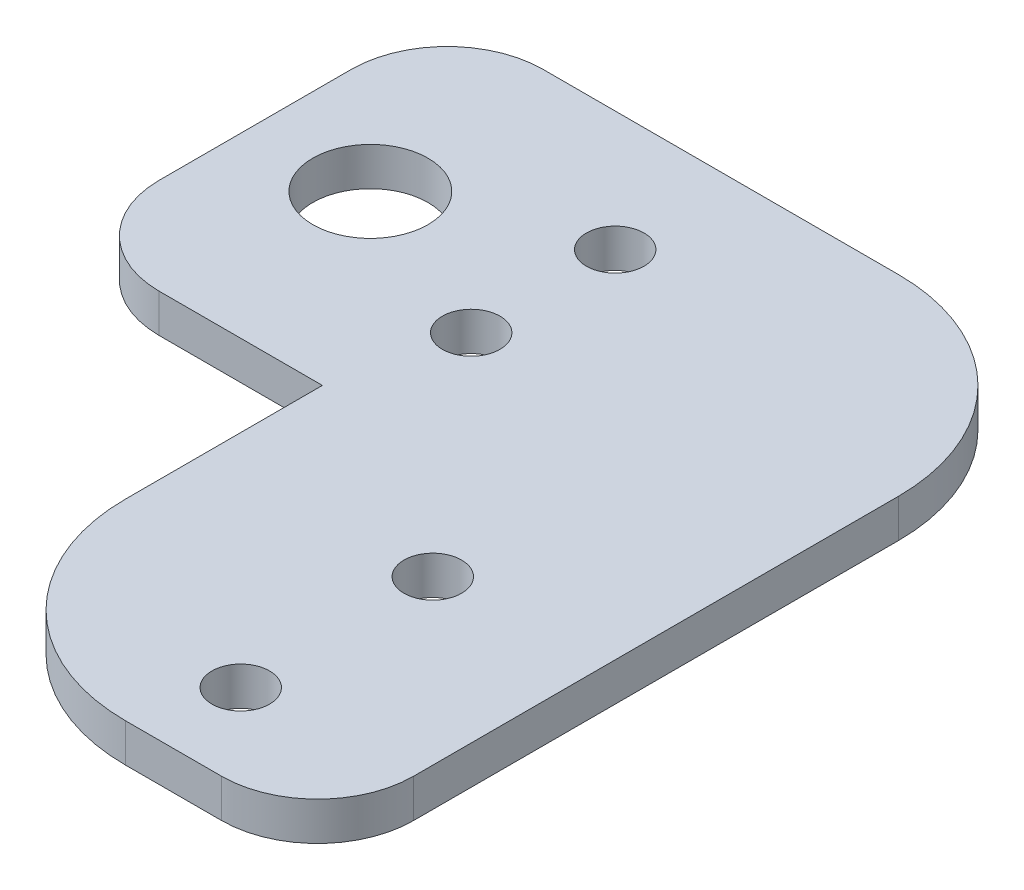
SolidWorks part; units mm, degrees
ref_plane "Front Plane" through (0, 0, 0) normal (0, 0, 1) x (1, 0, 0)
ref_plane "Top Plane" through (0, 0, 0) normal (0, 1, 0) x (1, 0, 0)
ref_plane "Right Plane" through (0, 0, 0) normal (1, 0, 0) x (0, 0, -1)
sketch "Sketch1" plane through (0, 0, 0) normal (0, 1, 0) x (1, 0, 0)
  line L1 (-12.5, 10) -> (12.5, 10)
  line L2 (-12.5, 10) -> (-12.5, -10)
  line L3 (-12.5, -10) -> (12.5, -10)
  line L4 (12.5, 10) -> (12.5, -10)
  line L5 (-12.5, 10) -> (12.5, -10) construction
  line L6 (-12.5, -10) -> (12.5, 10) construction
  point P0 (0, 0)
  point P5 (0, 0)
  dimension "D1" = 25
  dimension "D2" = 20
extrude "Boss-Extrude1" add sketch "Sketch1" along normal blind 2
sketch "Sketch2" plane through (0, 2, 0) normal (0, 1, 0) x (1, 0, 0)
  line L0 (12.5, -10) -> (12.5, 10) construction
  circle A0 centre (-6.5, 0) radius 1.5
  circle A1 centre (2.5, 3.75) radius 1.5
  circle A2 centre (2.5, -3.75) radius 1.5
  point P9 (0, 0)
  dimension "D1" = 3
  dimension "D4" = 3
  dimension "D5" = 3
  dimension "D2" = 19
  dimension "D3" = 7.5
  dimension "D6" = 3.75
  dimension "D7" = 9
extrude "Cut-Extrude1" cut sketch "Sketch2" against normal up to next
sketch "Sketch3" plane through (0, 0, 0) normal (0, -1, 0) x (-1, 0, 0)
  circle A0 centre (6.5, 0) radius 3
  circle A1 centre (6.5, 0) radius 1.5 construction
  dimension "D1" = 6
extrude "Cut-Extrude2" cut sketch "Sketch3" against normal up to next
sketch "Sketch4" plane through (0, 2, 0) normal (0, 1, 0) x (1, 0, 0)
  line L1 (21, -30.25) -> (1, -30.25)
  line L2 (21, -30.25) -> (21, -5.25)
  line L3 (21, -5.25) -> (1, -5.25)
  line L4 (1, -30.25) -> (1, -5.25)
  line L5 (21, -30.25) -> (1, -5.25) construction
  line L6 (21, -5.25) -> (1, -30.25) construction
  circle A0 centre (2.5, -3.75) radius 1.5 construction
  point P0 (11, -17.75)
  dimension "D1" = 25
  dimension "D2" = 20
extrude "Boss-Extrude2" add sketch "Sketch4" against normal blind 2
sketch "Sketch5" plane through (0, 2, 0) normal (0, 1, 0) x (1, 0, 0)
  line L0 (12.5, 10) -> (12.5, -5.25)
  line L1 (12.5, -5.25) -> (21, -5.25)
  line L2 (21, -5.25) -> (12.5, 10)
  point P4 (0, 0)
  point P6 (0, 0)
  point P8 (0, 0)
  point P10 (0, 0)
extrude "Boss-Extrude3" add sketch "Sketch5" against normal blind 2
sketch "Sketch6" plane through (0, 2, 0) normal (0, 1, 0) x (1, 0, 0)
  circle A0 centre (12.5, -15.75) radius 1.5
  circle A1 centre (2.5, -3.75) radius 1.5 construction
  circle A2 centre (12.5, -25.75) radius 1.5
  point P6 (0, 0)
  point P7 (0, 0)
  dimension "D1" = 3
  dimension "D2" = 10
  dimension "D4" = 3
  dimension "D3" = 12
  dimension "D5" = 10
extrude "Cut-Extrude3" cut sketch "Sketch6" against normal blind 2
sketch "Sketch7" plane through (0, 2, 0) normal (0, 1, 0) x (1, 0, 0)
  line L1 (12.5, -5.25) -> (21, -5.25)
  line L2 (12.5, -5.25) -> (12.5, 10)
  line L3 (12.5, 10) -> (21, 10)
  line L4 (21, -5.25) -> (21, 10)
  line L5 (12.5, -5.25) -> (21, 10) construction
  line L6 (12.5, 10) -> (21, -5.25) construction
  point P0 (16.75, 2.375)
  point P5 (0, 0)
  point P7 (0, 0)
extrude "Boss-Extrude5" add sketch "Sketch7" against normal blind 2
fillet "Fillet1" radius 10 2 edges at (21, 1, -10) (1, 1, 30.25)
fillet "Fillet2" radius 5 3 edges at (-12.5, 1, -10) (-12.5, 1, 10) (21, 1, 30.25)
